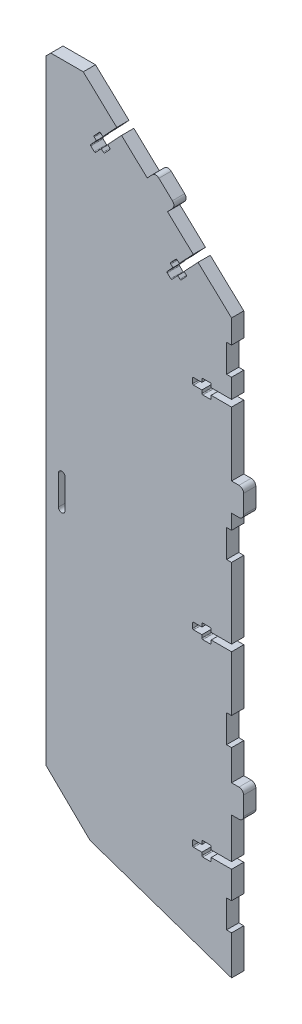
SolidWorks part; units mm, degrees
ref_plane "Front Plane" through (0, 0, 0) normal (0, 0, 1) x (1, 0, 0)
ref_plane "Top Plane" through (0, 0, 0) normal (0, 1, 0) x (1, 0, 0)
ref_plane "Right Plane" through (0, 0, 0) normal (1, 0, 0) x (0, 0, -1)
sketch "Model" plane through (0, 0, 0) normal (0, 0, 1) x (1, 0, 0)
  line L0 (-89.8155, 173.3473) -> (-89.8635, 172.9526)
  line L1 (-89.8635, 172.9526) -> (-90.0068, 172.5841)
  line L2 (-90.0068, 189.9856) -> (-89.8642, 189.6199)
  line L3 (-89.8642, 189.6199) -> (-89.8155, 189.2223)
  line L4 (-2.7, 21.1) -> (0, 21.1)
  line L5 (0, 0) -> (0, 21.1)
  line L6 (-76.35, 26.1117) -> (0, 0)
  line L7 (-100, 49.2) -> (-76.35, 26.1117)
  line L8 (-100, 380.9) -> (-100, 49.2)
  line L9 (-97.5, 383.4) -> (-100, 380.9)
  line L10 (-80, 383.4) -> (-97.5, 383.4)
  line L11 (-61.9203, 366.4503) -> (-80, 383.4)
  line L12 (-69.4437, 358.4254) -> (-61.9203, 366.4503)
  line L13 (-70.6, 359.5094) -> (-69.4437, 358.4254)
  line L14 (-74.0425, 356.5685) -> (-71.3067, 359.4866)
  line L15 (-72.8634, 354.7777) -> (-74.0197, 355.8617)
  line L16 (-75.9411, 351.4948) -> (-72.8634, 354.7777)
  line L17 (-74.058, 349.044) -> (-75.9183, 350.788)
  line L18 (-70.2735, 352.3497) -> (-73.3512, 349.0668)
  line L19 (-69.1172, 351.2657) -> (-70.2735, 352.3497)
  line L20 (-65.6747, 354.2066) -> (-68.4105, 351.2885)
  line L21 (-66.8538, 355.9974) -> (-65.6975, 354.9133)
  line L22 (-59.3305, 364.0223) -> (-66.8538, 355.9974)
  line L23 (-45.4692, 351.0274) -> (-59.3305, 364.0223)
  line L24 (-45.4692, 351.0274) -> (-42.7335, 353.9456)
  line L25 (-39.1998, 354.0596) -> (-31.9044, 347.2201)
  line L26 (-31.7904, 343.6865) -> (-34.5262, 340.7683)
  line L27 (-20.665, 327.7734) -> (-34.5262, 340.7683)
  line L28 (-28.1883, 319.7485) -> (-20.665, 327.7734)
  line L29 (-29.3447, 320.8326) -> (-28.1883, 319.7485)
  line L30 (-32.7872, 317.8916) -> (-30.0514, 320.8098)
  line L31 (-31.608, 316.1008) -> (-32.7644, 317.1849)
  line L32 (-34.6858, 312.8179) -> (-31.608, 316.1008)
  line L33 (-32.8027, 310.3671) -> (-34.663, 312.1112)
  line L34 (-29.0182, 313.6728) -> (-32.0959, 310.3899)
  line L35 (-27.8619, 312.5888) -> (-29.0182, 313.6728)
  line L36 (-24.4194, 315.5297) -> (-27.1551, 312.6116)
  line L37 (-25.5985, 317.3205) -> (-24.4422, 316.2365)
  line L38 (-18.0751, 325.3454) -> (-25.5985, 317.3205)
  line L39 (0, 308.4) -> (-18.0751, 325.3454)
  line L40 (0, 295.7) -> (0, 308.4)
  line L41 (0, 295.7) -> (-2.7, 295.7)
  line L42 (-2.7, 295.7) -> (-2.7, 280.7)
  line L43 (-2.7, 280.7) -> (0, 280.7)
  line L44 (0, 270.3) -> (0, 280.7)
  line L45 (-11, 270.3) -> (0, 270.3)
  line L46 (-11, 271.885) -> (-11, 270.3)
  line L47 (-15.5, 272.385) -> (-11.5, 272.385)
  line L48 (-16, 270.3) -> (-16, 271.885)
  line L49 (-20.5, 270.3) -> (-16, 270.3)
  line L50 (-21, 267.25) -> (-21, 269.8)
  line L51 (-16, 266.75) -> (-20.5, 266.75)
  line L52 (-16, 265.165) -> (-16, 266.75)
  line L53 (-11.5, 264.665) -> (-15.5, 264.665)
  line L54 (-11, 266.75) -> (-11, 265.165)
  line L55 (0, 266.75) -> (-11, 266.75)
  line L56 (0, 232.2) -> (0, 266.75)
  line L57 (4, 232.2) -> (0, 232.2)
  line L58 (6.5, 219.7) -> (6.5, 229.7)
  line L59 (4, 217.2) -> (0, 217.2)
  line L60 (0, 209.1667) -> (0, 217.2)
  line L61 (0, 209.1667) -> (-2.7, 209.1667)
  line L62 (-2.7, 209.1667) -> (-2.7, 194.1667)
  line L63 (-2.7, 194.1667) -> (0, 194.1667)
  line L64 (0, 155.975) -> (0, 194.1667)
  line L65 (-11, 155.975) -> (0, 155.975)
  line L66 (-11, 157.56) -> (-11, 155.975)
  line L67 (-15.5, 158.06) -> (-11.5, 158.06)
  line L68 (-16, 155.975) -> (-16, 157.56)
  line L69 (-20.5, 155.975) -> (-16, 155.975)
  line L70 (-21, 152.925) -> (-21, 155.475)
  line L71 (-16, 152.425) -> (-20.5, 152.425)
  line L72 (-16, 150.84) -> (-16, 152.425)
  line L73 (-11.5, 150.34) -> (-15.5, 150.34)
  line L74 (-11, 152.425) -> (-11, 150.84)
  line L75 (0, 152.425) -> (-11, 152.425)
  line L76 (0, 122.6333) -> (0, 152.425)
  line L77 (0, 122.6333) -> (-2.7, 122.6333)
  line L78 (-2.7, 122.6333) -> (-2.7, 107.6333)
  line L79 (-2.7, 107.6333) -> (0, 107.6333)
  line L80 (0, 91.2) -> (0, 107.6333)
  line L81 (4, 91.2) -> (0, 91.2)
  line L82 (6.5, 78.7) -> (6.5, 88.7)
  line L83 (4, 76.2) -> (0, 76.2)
  line L84 (0, 54.35) -> (0, 76.2)
  line L85 (-11, 54.35) -> (0, 54.35)
  line L86 (-11, 55.935) -> (-11, 54.35)
  line L87 (-15.5, 56.435) -> (-11.5, 56.435)
  line L88 (-16, 54.35) -> (-16, 55.935)
  line L89 (-20.5, 54.35) -> (-16, 54.35)
  line L90 (-21, 51.3) -> (-21, 53.85)
  line L91 (-16, 50.8) -> (-20.5, 50.8)
  line L92 (-16, 49.215) -> (-16, 50.8)
  line L93 (-11.5, 48.715) -> (-15.5, 48.715)
  line L94 (-11, 50.8) -> (-11, 49.215)
  line L95 (0, 50.8) -> (-11, 50.8)
  line L96 (0, 36.1) -> (0, 50.8)
  line L97 (0, 36.1) -> (-2.7, 36.1)
  line L98 (-2.7, 36.1) -> (-2.7, 21.1)
  line L99 (-89.8155, 189.2223) -> (-89.8155, 173.3473)
  line L100 (-93.3843, 173.3473) -> (-93.3843, 189.2223)
  arc A0 (-70.6, 359.5094) -> (-71.3067, 359.4866) centre (-70.942, 359.1447) ccw
  arc A1 (-74.0425, 356.5685) -> (-74.0197, 355.8617) centre (-73.6777, 356.2265) ccw
  arc A2 (-75.9411, 351.4948) -> (-75.9183, 350.788) centre (-75.5763, 351.1528) ccw
  arc A3 (-74.058, 349.044) -> (-73.3512, 349.0668) centre (-73.716, 349.4088) ccw
  arc A4 (-69.1172, 351.2657) -> (-68.4105, 351.2885) centre (-68.7752, 351.6304) ccw
  arc A5 (-65.6747, 354.2066) -> (-65.6975, 354.9133) centre (-66.0395, 354.5486) ccw
  arc A6 (-39.1998, 354.0596) -> (-42.7335, 353.9456) centre (-40.9096, 352.2357) ccw
  arc A7 (-31.7904, 343.6865) -> (-31.9044, 347.2201) centre (-33.6143, 345.3963) ccw
  arc A8 (-29.3447, 320.8326) -> (-30.0514, 320.8098) centre (-29.6866, 320.4678) ccw
  arc A9 (-32.7872, 317.8916) -> (-32.7644, 317.1849) centre (-32.4224, 317.5496) ccw
  arc A10 (-34.6858, 312.8179) -> (-34.663, 312.1112) centre (-34.321, 312.4759) ccw
  arc A11 (-32.8027, 310.3671) -> (-32.0959, 310.3899) centre (-32.4607, 310.7319) ccw
  arc A12 (-27.8619, 312.5888) -> (-27.1551, 312.6116) centre (-27.5199, 312.9536) ccw
  arc A13 (-24.4194, 315.5297) -> (-24.4422, 316.2365) centre (-24.7841, 315.8717) ccw
  arc A14 (-11, 271.885) -> (-11.5, 272.385) centre (-11.5, 271.885) ccw
  arc A15 (-15.5, 272.385) -> (-16, 271.885) centre (-15.5, 271.885) ccw
  arc A16 (-20.5, 270.3) -> (-21, 269.8) centre (-20.5, 269.8) ccw
  arc A17 (-21, 267.25) -> (-20.5, 266.75) centre (-20.5, 267.25) ccw
  arc A18 (-16, 265.165) -> (-15.5, 264.665) centre (-15.5, 265.165) ccw
  arc A19 (-11.5, 264.665) -> (-11, 265.165) centre (-11.5, 265.165) ccw
  arc A20 (6.5, 229.7) -> (4, 232.2) centre (4, 229.7) ccw
  arc A21 (4, 217.2) -> (6.5, 219.7) centre (4, 219.7) ccw
  arc A22 (-11, 157.56) -> (-11.5, 158.06) centre (-11.5, 157.56) ccw
  arc A23 (-15.5, 158.06) -> (-16, 157.56) centre (-15.5, 157.56) ccw
  arc A24 (-20.5, 155.975) -> (-21, 155.475) centre (-20.5, 155.475) ccw
  arc A25 (-21, 152.925) -> (-20.5, 152.425) centre (-20.5, 152.925) ccw
  arc A26 (-16, 150.84) -> (-15.5, 150.34) centre (-15.5, 150.84) ccw
  arc A27 (-11.5, 150.34) -> (-11, 150.84) centre (-11.5, 150.84) ccw
  arc A28 (6.5, 88.7) -> (4, 91.2) centre (4, 88.7) ccw
  arc A29 (4, 76.2) -> (6.5, 78.7) centre (4, 78.7) ccw
  arc A30 (-11, 55.935) -> (-11.5, 56.435) centre (-11.5, 55.935) ccw
  arc A31 (-15.5, 56.435) -> (-16, 55.935) centre (-15.5, 55.935) ccw
  arc A32 (-20.5, 54.35) -> (-21, 53.85) centre (-20.5, 53.85) ccw
  arc A33 (-21, 51.3) -> (-20.5, 50.8) centre (-20.5, 51.3) ccw
  arc A34 (-16, 49.215) -> (-15.5, 48.715) centre (-15.5, 49.215) ccw
  arc A35 (-11.5, 48.715) -> (-11, 49.215) centre (-11.5, 49.215) ccw
  arc A36 (-93.3843, 173.3473) -> (-90.0068, 172.5841) centre (-91.6093, 173.3473) ccw
  arc A37 (-90.0068, 189.9856) -> (-93.3843, 189.2223) centre (-91.6093, 189.2223) ccw
extrude "Boss-Extrude1" add sketch "Model" along normal blind 6.6
